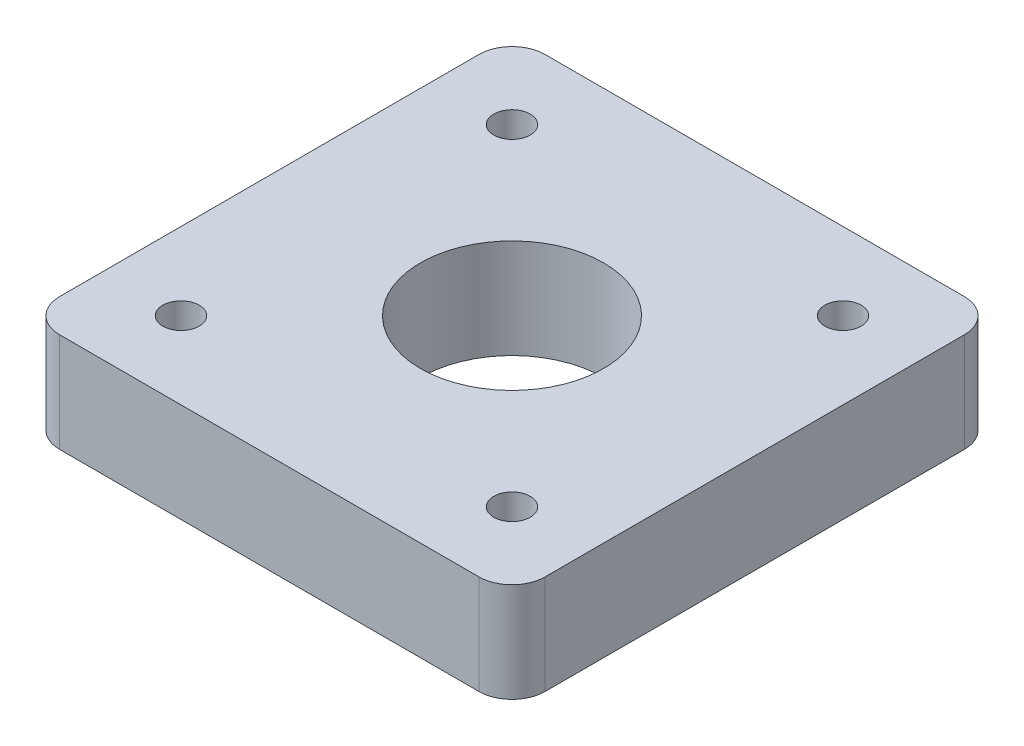
SolidWorks part; units mm, degrees
ref_plane "前视基准面" through (0, 0, 0) normal (0, 0, 1) x (1, 0, 0)
ref_plane "上视基准面" through (0, 0, 0) normal (0, 1, 0) x (1, 0, 0)
ref_plane "右视基准面" through (0, 0, 0) normal (1, 0, 0) x (0, 0, -1)
other "Configuration Table"
sketch "草图1" plane through (0, 0, 0) normal (0, 0, 1) x (1, 0, 0)
  line L0 (0, 0) -> (44, 0)
  line L1 (44, 0) -> (44, 9)
  line L2 (44, 9) -> (0, 9)
  line L3 (0, 9) -> (0, 0)
  dimension "width" = 44
  dimension "height" = 9
extrude "Raised_flange" add sketch "草图1" along normal blind 44
fillet "Fillet" radius 3 4 edges at (0, 4.5, 0) (44, 4.5, 0) (0, 4.5, 44) (44, 4.5, 44)
sketch "草图2" plane through (0, 9, 0) normal (0, 1, 0) x (1, 0, 0)
  circle A0 centre (22, -22) radius 8.3
  dimension "diameter" = 16.6
  dimension "x" = 22
  dimension "y" = 22
extrude "Flange_hole" cut sketch "草图2" against normal through all
sketch "草图3" plane through (0, 9, 0) normal (0, 1, 0) x (1, 0, 0)
  circle A0 centre (7, -7) radius 1.65
  dimension "diameter" = 3.3
  dimension "x" = 7
  dimension "y" = 7
extrude "切除-拉伸2" cut sketch "草图3" against normal through all
sketch "草图4" plane through (0, 9, 0) normal (0, 1, 0) x (1, 0, 0)
  circle A0 centre (7, -37) radius 1.65
  dimension "diameter" = 3.3
  dimension "x" = 7
  dimension "y" = 37
extrude "切除-拉伸3" cut sketch "草图4" against normal through all
sketch "草图5" plane through (0, 9, 0) normal (0, 1, 0) x (1, 0, 0)
  circle A0 centre (37, -7) radius 1.65
  dimension "diameter" = 3.3
  dimension "x" = 37
  dimension "y" = 7
extrude "切除-拉伸4" cut sketch "草图5" against normal through all
sketch "草图6" plane through (0, 9, 0) normal (0, 1, 0) x (1, 0, 0)
  circle A0 centre (37, -37) radius 1.65
  dimension "diameter" = 3.3
  dimension "x" = 37
  dimension "y" = 37
extrude "切除-拉伸5" cut sketch "草图6" against normal through all
